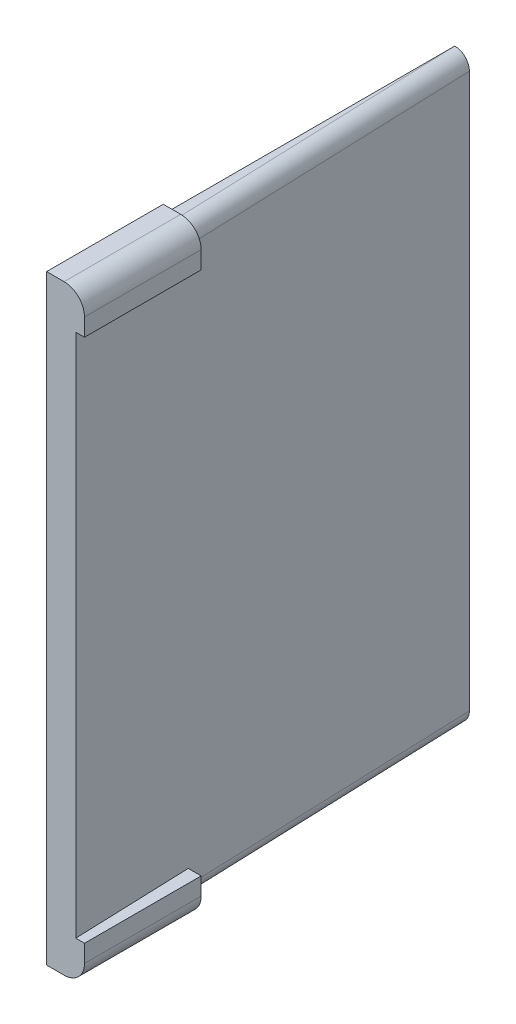
SolidWorks part; units mm, degrees
material "ABS"
ref_plane "Alzado" through (0, 0, 0) normal (0, 0, 1) x (1, 0, 0)
ref_plane "Planta" through (0, 0, 0) normal (0, 1, 0) x (1, 0, 0)
ref_plane "Vista lateral" through (0, 0, 0) normal (1, 0, 0) x (0, 0, -1)
sketch "Croquis1" plane through (0, 0, 0) normal (0, 1, 0) x (1, 0, 0)
  line L0 (5, 140) -> (10, 0)
  line L1 (0, 0) -> (5, 0)
  line L2 (0, 0) -> (0, 140)
  line L3 (0, 140) -> (5, 140)
  line L5 (10, 0) -> (5, 0)
  dimension "D1" = 140
  dimension "D2" = 5
  dimension "D3" = 5
extrude "Saliente-Extruir1" add sketch "Croquis1" along normal blind 200
sketch "Croquis5" plane through (0, 0, 0) normal (-1, 0, 0) x (0, 0, 1)
  line L0 (0, 200) -> (0, 0) construction
  line L1 (0, 190) -> (-40, 190)
  line L2 (0, 190) -> (0, 203)
  line L3 (0, 203) -> (-40, 203)
  line L4 (-40, 190) -> (-40, 203)
  line L5 (-140, 200) -> (0, 200) construction
  line L6 (0, 10) -> (-40, 10)
  line L7 (0, 10) -> (0, -3)
  line L8 (0, -3) -> (-40, -3)
  line L9 (-40, 10) -> (-40, -3)
  line L10 (-140, 0) -> (0, 0) construction
  dimension "D1" = 40
  dimension "D2" = 40
  dimension "D3" = 13
  dimension "D4" = 10
  dimension "D5" = 10
  dimension "D6" = 13
extrude "Saliente-Extruir4" add sketch "Croquis5" against normal blind 13
fillet "Redondeo9" radius 7 2 edges at (13, -3, -20) (13, 203, -20)
fillet "Redondeo11" radius 5 2 edges at (6.7857, 0, -90) (6.7857, 200, -90)
